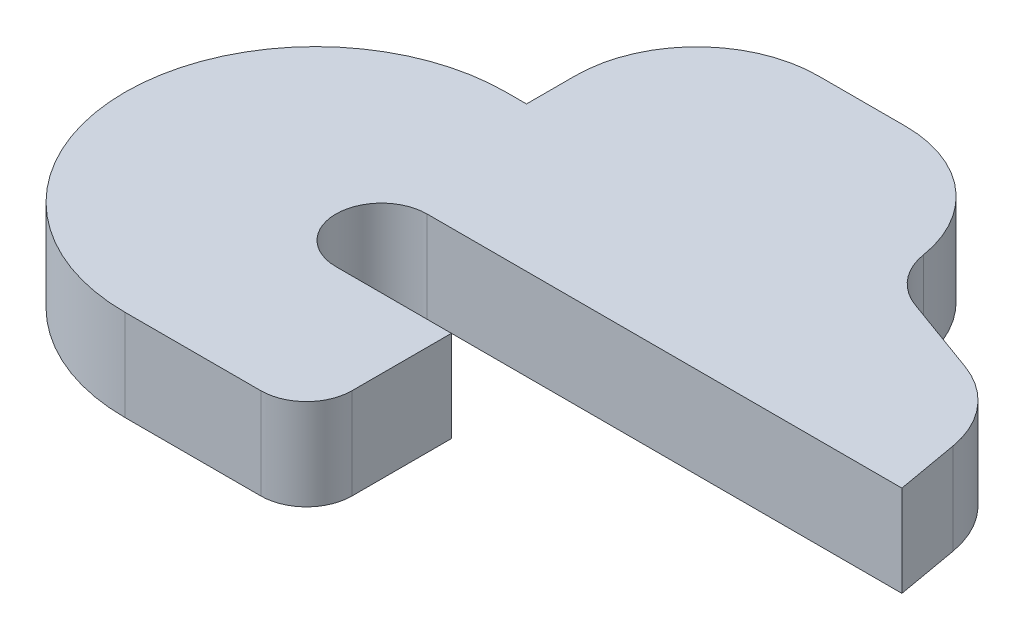
SolidWorks part; units mm, degrees
ref_plane "Front Plane" through (0, 0, 0) normal (0, 0, 1) x (1, 0, 0)
ref_plane "Top Plane" through (0, 0, 0) normal (0, 1, 0) x (1, 0, 0)
ref_plane "Right Plane" through (0, 0, 0) normal (1, 0, 0) x (0, 0, -1)
sketch "Sketch1" plane through (0, 0, 0) normal (0, 1, 0) x (1, 0, 0)
  line L0 (0, 0) -> (-3.8, 0)
  line L1 (-3.8, 3) -> (11.82, 3)
  line L2 (11.82, 3) -> (11.4588, 5.0483)
  line L5 (1.5789, 13.37) -> (-1.3, 13.37)
  line L6 (-5.3, 9.37) -> (-5.3, 7.77)
  line L7 (-5.3, 7.77) -> (-5.97, 7.77)
  line L9 (0, -3.27) -> (0, 0)
  line L10 (-5.97, -4.77) -> (-1.5, -4.77)
  line L11 (6.82, 8.4386) -> (9.401, 7.5)
  arc A0 (-3.8, 0) -> (-3.8, 3) centre (-3.8, 1.5) cw
  arc A1 (11.4588, 5.0483) -> (9.401, 7.5) centre (8.3074, 4.4927) ccw
  arc A4 (-1.3, 13.37) -> (-5.3, 9.37) centre (-1.3, 9.37) ccw
  arc A5 (-5.97, 7.77) -> (-5.97, -4.77) centre (-5.97, 1.5) ccw
  arc A8 (1.5789, 13.37) -> (5.5286, 10.0021) centre (1.5789, 9.37) cw
  arc A9 (6.82, 8.4386) -> (5.5286, 10.0021) centre (7.5035, 10.3182) cw
  arc A10 (-1.5, -4.77) -> (0, -3.27) centre (-1.5, -3.27) ccw
  point P13 (5.5512, 8.9)
  point P43 (-12.24, 1.5)
  point P44 (-5.3, 1.5)
  dimension "D1" = 5.6
  dimension "10.9" = 6.27
  dimension "D4" = 1.5
  dimension "4" = 4
  dimension "3" = 3.2
  dimension "D10" = 2
  dimension "D11" = 1.5
  dimension "D2" = 4
  dimension "D3" = 4.47
  dimension "3.65" = 4.5
  dimension "13.48" = 15.62
  dimension "80" = 80
  dimension "D8" = 6.94
  dimension "D9" = 3.8
  dimension "5" = 5
extrude "Boss-Extrude2" add sketch "Sketch1" along normal blind 3
